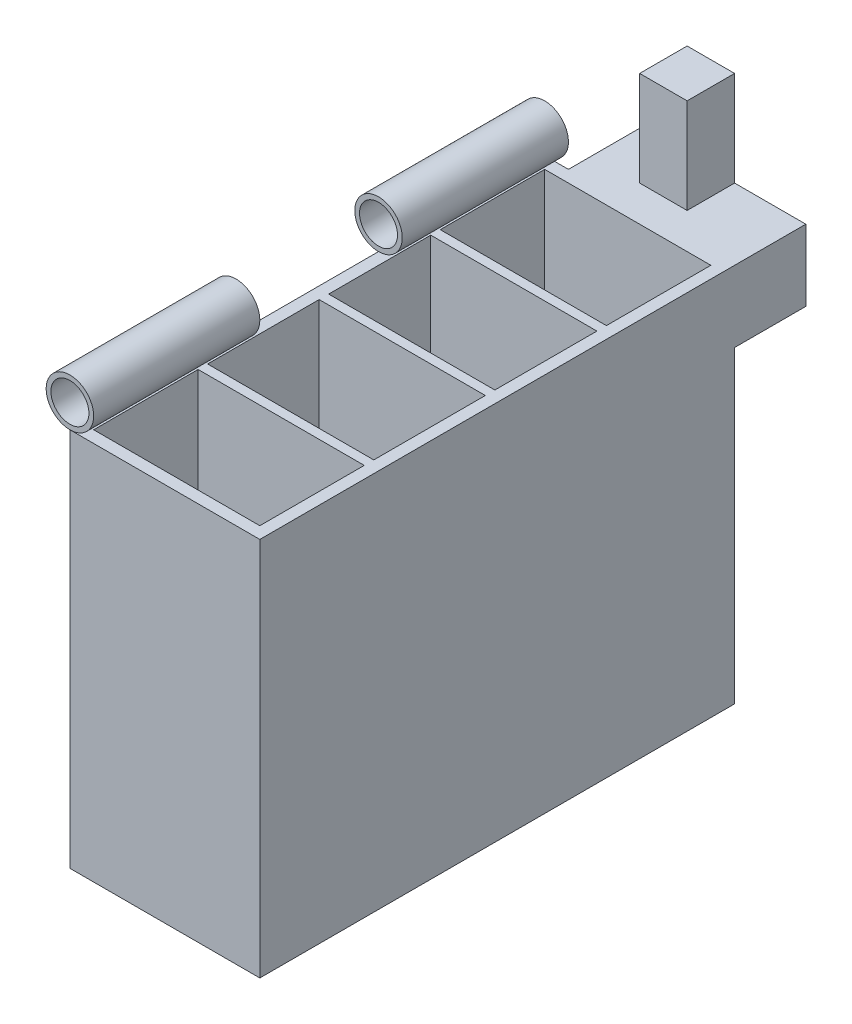
SolidWorks part; units mm, degrees
ref_plane "Front Plane" through (0, 0, 0) normal (0, 0, 1) x (1, 0, 0)
ref_plane "Top Plane" through (0, 0, 0) normal (0, 1, 0) x (1, 0, 0)
ref_plane "Right Plane" through (0, 0, 0) normal (1, 0, 0) x (0, 0, -1)
sketch "Sketch1" plane through (0, 0, 0) normal (0, 0, 1) x (1, 0, 0)
  line L5 (-20, 40) -> (20, 40)
  line L6 (-20, 40) -> (-20, -40)
  line L7 (-20, -40) -> (20, -40)
  line L8 (20, 40) -> (20, -40)
  line L9 (-20, 40) -> (20, -40) construction
  line L10 (-20, -40) -> (20, 40) construction
  point P0 (0, 0)
  dimension "D1" = 40
  dimension "D2" = 80
extrude "Boss-Extrude1" add sketch "Sketch1" along normal mid plane 100
sketch "Sketch2" plane through (0, 40, 0) normal (0, 1, 0) x (1, 0, 0)
  line L0 (20, -50) -> (-20, -50) construction
  line L1 (-17.5, 47.5) -> (17.5, 47.5)
  line L2 (-17.5, 47.5) -> (-17.5, -47.5)
  line L3 (-17.5, -47.5) -> (17.5, -47.5)
  line L4 (17.5, 47.5) -> (17.5, -47.5)
  line L5 (-17.5, 47.5) -> (17.5, -47.5) construction
  line L6 (-17.5, -47.5) -> (17.5, 47.5) construction
  line L7 (17.5, 25.5) -> (-17.5, 25.5)
  line L8 (17.5, 25.5) -> (17.5, 23.5)
  line L9 (17.5, 23.5) -> (-17.5, 23.5)
  line L10 (-17.5, 25.5) -> (-17.5, 23.5)
  line L11 (17.5, 2) -> (-17.5, 2)
  line L12 (17.5, 2) -> (17.5, 0)
  line L13 (17.5, 0) -> (-17.5, 0)
  line L14 (-17.5, 2) -> (-17.5, 0)
  line L15 (17.5, -23.5) -> (-17.5, -23.5)
  line L16 (17.5, -23.5) -> (17.5, -25.5)
  line L17 (17.5, -25.5) -> (-17.5, -25.5)
  line L18 (-17.5, -23.5) -> (-17.5, -25.5)
  line L19 (20, 50) -> (-20, 50) construction
  line L20 (-20, -50) -> (-20, 50) construction
  point P0 (0, 0)
  dimension "D1" = 95
  dimension "D2" = 35
  dimension "D3" = 35
  dimension "D4" = 22
  dimension "D5" = 2
  dimension "D6" = 2
  dimension "D7" = 2
  dimension "D8" = 22
  dimension "D9" = 2.5
  dimension "D10" = 2.5
extrude "Cut-Extrude2" cut sketch "Sketch2" against normal blind 75 contours L4 L17 L2 L3 | L15 L4 L13 L2 | L11 L4 L9 L2 | L7 L4 L1 L2
sketch "Sketch7" plane through (-20, 0, 0) normal (-1, 0, 0) x (0, 0, 1)
  line L1 (50, 40) -> (50, 45) construction
  line L3 (50, 45) -> (15, 45)
  dimension "D3" = 35
  dimension "D4" = 5
revolve "Revolve-Thin1" add sketch "Sketch7" angle 360 about L3 wall 5
sketch "Sketch9" plane through (0, 0, 50) normal (0, 0, 1) x (1, 0, 0)
  circle A0 centre (-20, 45) radius 4
  circle A1 centre (-20, 45) radius 5 construction
  dimension "D1" = 8
extrude "Cut-Extrude3" cut sketch "Sketch9" against normal up to next (35 mm away) contours A0
sketch "Sketch12" plane through (0, 0, -50) normal (0, 0, -1) x (-1, 0, 0)
  circle A0 centre (20, 45) radius 5
  circle A1 centre (20, 45) radius 4
  dimension "D1" = 8
  dimension "D2" = 10
extrude "Boss-Extrude2" add sketch "Sketch12" against normal blind 35 separate body
sketch "Sketch14" plane through (20, 0, 0) normal (1, 0, 0) x (0, 0, -1)
  line L1 (50, 40) -> (65, 40)
  line L2 (50, 40) -> (50, 25)
  line L3 (50, 25) -> (65, 25)
  line L4 (65, 40) -> (65, 25)
  dimension "D1" = 15
  dimension "D2" = 15
extrude "Boss-Extrude3" add sketch "Sketch14" against normal blind 35
sketch "Sketch15" plane through (0, 0, -65) normal (0, 0, -1) x (-1, 0, 0)
  line L0 (15, 25) -> (-20, 25) construction
  line L1 (-5, 25) -> (5, 25)
  line L2 (-5, 25) -> (-5, 60)
  line L3 (-5, 60) -> (5, 60)
  line L4 (5, 25) -> (5, 60)
  line L5 (-20, 25) -> (-20, 40) construction
  line L6 (15, 40) -> (-20, 40) construction
  point P6 (5.1538, 60)
  point P9 (5, 29.806)
  dimension "D1" = 35
  dimension "D2" = 10
  dimension "D3" = 15
extrude "Boss-Extrude4" add sketch "Sketch15" against normal blind 10
